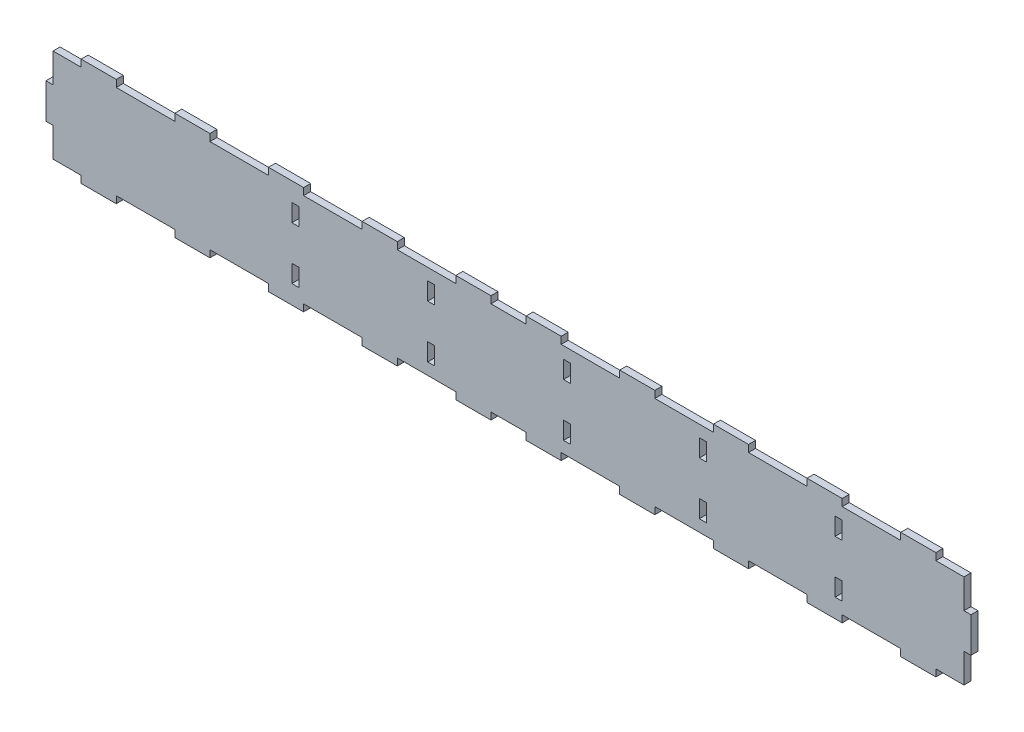
SolidWorks part; units mm, degrees
material "Acrylic (Medium-high impact)"
ref_plane "Front Plane" through (0, 0, 0) normal (0, 0, 1) x (1, 0, 0)
ref_plane "Top Plane" through (0, 0, 0) normal (0, 1, 0) x (1, 0, 0)
ref_plane "Right Plane" through (0, 0, 0) normal (1, 0, 0) x (0, 0, -1)
sketch "Sketch1" plane through (0, 0, 0) normal (0, 0, 1) x (1, 0, 0)
  line L1 (395, 40) -> (-395, 40)
  line L2 (395, 40) -> (395, -40)
  line L3 (395, -40) -> (-395, -40)
  line L4 (-395, 40) -> (-395, -40)
  line L5 (395, 40) -> (-395, -40) construction
  line L6 (395, -40) -> (-395, 40) construction
  point P0 (0, 0)
  dimension "D1" = 790
  dimension "D2" = 80
extrude "Boss-Extrude1" add sketch "Sketch1" along normal blind 6
sketch "Sketch2" plane through (0, 0, 0) normal (0, 0, -1) x (-1, 0, 0)
  line L0 (389, -46) -> (389, -15) construction
  line L1 (395, 40) -> (389, 40)
  line L2 (395, 40) -> (395, 15)
  line L3 (395, 15) -> (389, 15)
  line L4 (389, 40) -> (389, 15)
  line L5 (0, 0) -> (0, 142.203) construction
  line L6 (395, -40) -> (389, -40)
  line L7 (395, -40) -> (395, -15)
  line L8 (395, -15) -> (389, -15)
  line L9 (389, -40) -> (389, -15)
  line L10 (-389, -40) -> (-389, -15)
  line L11 (-395, -15) -> (-389, -15)
  line L12 (-395, -40) -> (-395, -15)
  line L13 (-395, -40) -> (-389, -40)
  line L14 (-389, 40) -> (-389, 15)
  line L15 (-395, 15) -> (-389, 15)
  line L16 (-395, 40) -> (-395, 15)
  line L17 (-395, 40) -> (-389, 40)
  line L18 (69, -15) -> (63, -15)
  line L19 (63, -15) -> (63, -30)
  line L20 (63, -30) -> (69, -30)
  line L21 (69, -30) -> (69, -15)
  line L22 (185, -15) -> (179, -15)
  line L23 (179, -15) -> (179, -30)
  line L24 (179, -30) -> (185, -30)
  line L25 (185, -30) -> (185, -15)
  line L26 (185, -15) -> (179, -15)
  line L27 (179, -15) -> (179, -30)
  line L28 (179, -30) -> (185, -30)
  line L29 (185, -30) -> (185, -15)
  line L30 (185, 30) -> (179, 30)
  line L31 (179, 30) -> (179, 15)
  line L32 (179, 15) -> (185, 15)
  line L33 (185, 15) -> (185, 30)
  line L34 (185, 30) -> (179, 30)
  line L35 (179, 30) -> (179, 15)
  line L36 (179, 15) -> (185, 15)
  line L37 (185, 15) -> (185, 30)
  line L38 (69, 30) -> (63, 30)
  line L39 (63, 30) -> (63, 15)
  line L40 (63, 15) -> (69, 15)
  line L41 (69, 15) -> (69, 30)
  line L42 (-47, -15) -> (-53, -15)
  line L43 (-53, -15) -> (-53, -30)
  line L44 (-53, -30) -> (-47, -30)
  line L45 (-47, -30) -> (-47, -15)
  line L46 (-47, 30) -> (-53, 30)
  line L47 (-53, 30) -> (-53, 15)
  line L48 (-53, 15) -> (-47, 15)
  line L49 (-47, 15) -> (-47, 30)
  line L50 (-163, -15) -> (-169, -15)
  line L51 (-169, -15) -> (-169, -30)
  line L52 (-169, -30) -> (-163, -30)
  line L53 (-163, -30) -> (-163, -15)
  line L54 (-163, 30) -> (-169, 30)
  line L55 (-169, 30) -> (-169, 15)
  line L56 (-169, 15) -> (-163, 15)
  line L57 (-163, 15) -> (-163, 30)
  line L58 (-279, -15) -> (-285, -15)
  line L59 (-285, -15) -> (-285, -30)
  line L60 (-285, -30) -> (-279, -30)
  line L61 (-279, -30) -> (-279, -15)
  line L62 (-279, 30) -> (-285, 30)
  line L63 (-285, 30) -> (-285, 15)
  line L64 (-285, 15) -> (-279, 15)
  line L65 (-279, 15) -> (-279, 30)
  dimension "D1" = 25
  dimension "D2" = 25
  dimension "D3" = 0
  dimension "D4" = 0
extrude "Cut-Extrude1" cut sketch "Sketch2" against normal blind 6
sketch "Sketch3" plane through (0, 0, 0) normal (0, 0, -1) x (-1, 0, 0)
  line L0 (-45, -46) -> (-15, -46) construction
  line L1 (-15, -46) -> (-15, -40) construction
  line L2 (-15, -40) -> (-45, -40) construction
  line L3 (-45, -40) -> (-45, -46) construction
  line L4 (-15, 46) -> (-45, 46) construction
  line L5 (-45, 46) -> (-45, 40) construction
  line L6 (-45, 40) -> (-15, 40) construction
  line L7 (-15, 40) -> (-15, 46) construction
  line L8 (-45, -46) -> (-15, -46)
  line L9 (-15, -46) -> (-15, -40)
  line L10 (-15, -40) -> (-45, -40)
  line L11 (-45, -40) -> (-45, -46)
  line L12 (-15, 46) -> (-45, 46)
  line L13 (-45, 46) -> (-45, 40)
  line L14 (-45, 40) -> (-15, 40)
  line L15 (-15, 40) -> (-15, 46)
  line L16 (-125, -46) -> (-95, -46)
  line L17 (-95, -46) -> (-95, -40)
  line L18 (-95, -40) -> (-125, -40)
  line L19 (-125, -40) -> (-125, -46)
  line L20 (-95, 46) -> (-125, 46)
  line L21 (-125, 46) -> (-125, 40)
  line L22 (-125, 40) -> (-95, 40)
  line L23 (-95, 40) -> (-95, 46)
  line L24 (-205, -46) -> (-175, -46)
  line L25 (-175, -46) -> (-175, -40)
  line L26 (-175, -40) -> (-205, -40)
  line L27 (-205, -40) -> (-205, -46)
  line L28 (-175, 46) -> (-205, 46)
  line L29 (-205, 46) -> (-205, 40)
  line L30 (-205, 40) -> (-175, 40)
  line L31 (-175, 40) -> (-175, 46)
  line L32 (-285, -46) -> (-255, -46)
  line L33 (-255, -46) -> (-255, -40)
  line L34 (-255, -40) -> (-285, -40)
  line L35 (-285, -40) -> (-285, -46)
  line L36 (-255, 46) -> (-285, 46)
  line L37 (-285, 46) -> (-285, 40)
  line L38 (-285, 40) -> (-255, 40)
  line L39 (-255, 40) -> (-255, 46)
  line L40 (-365, -46) -> (-335, -46)
  line L41 (-335, -46) -> (-335, -40)
  line L42 (-335, -40) -> (-365, -40)
  line L43 (-365, -40) -> (-365, -46)
  line L44 (-335, 46) -> (-365, 46)
  line L45 (-365, 46) -> (-365, 40)
  line L46 (-365, 40) -> (-335, 40)
  line L47 (-335, 40) -> (-335, 46)
  line L48 (0, 0) -> (0, 101.8547) construction
  line L49 (335, 40) -> (335, 46)
  line L50 (365, 40) -> (335, 40)
  line L51 (365, 46) -> (365, 40)
  line L52 (335, 46) -> (365, 46)
  line L53 (365, -40) -> (365, -46)
  line L54 (335, -40) -> (365, -40)
  line L55 (335, -46) -> (335, -40)
  line L56 (365, -46) -> (335, -46)
  line L57 (255, 40) -> (255, 46)
  line L58 (285, 40) -> (255, 40)
  line L59 (285, 46) -> (285, 40)
  line L60 (255, 46) -> (285, 46)
  line L61 (285, -40) -> (285, -46)
  line L62 (255, -40) -> (285, -40)
  line L63 (255, -46) -> (255, -40)
  line L64 (285, -46) -> (255, -46)
  line L65 (175, 40) -> (175, 46)
  line L66 (205, 40) -> (175, 40)
  line L67 (205, 46) -> (205, 40)
  line L68 (175, 46) -> (205, 46)
  line L69 (205, -40) -> (205, -46)
  line L70 (175, -40) -> (205, -40)
  line L71 (175, -46) -> (175, -40)
  line L72 (205, -46) -> (175, -46)
  line L73 (95, 40) -> (95, 46)
  line L74 (125, 40) -> (95, 40)
  line L75 (125, 46) -> (125, 40)
  line L76 (95, 46) -> (125, 46)
  line L77 (125, -40) -> (125, -46)
  line L78 (95, -40) -> (125, -40)
  line L79 (95, -46) -> (95, -40)
  line L80 (125, -46) -> (95, -46)
  line L81 (15, 40) -> (15, 46)
  line L82 (45, 40) -> (15, 40)
  line L83 (45, 46) -> (45, 40)
  line L84 (15, 46) -> (45, 46)
  line L85 (45, -40) -> (45, -46)
  line L86 (15, -40) -> (45, -40)
  line L87 (15, -46) -> (15, -40)
  line L88 (45, -46) -> (15, -46)
extrude "Boss-Extrude2" add sketch "Sketch3" against normal blind 6
